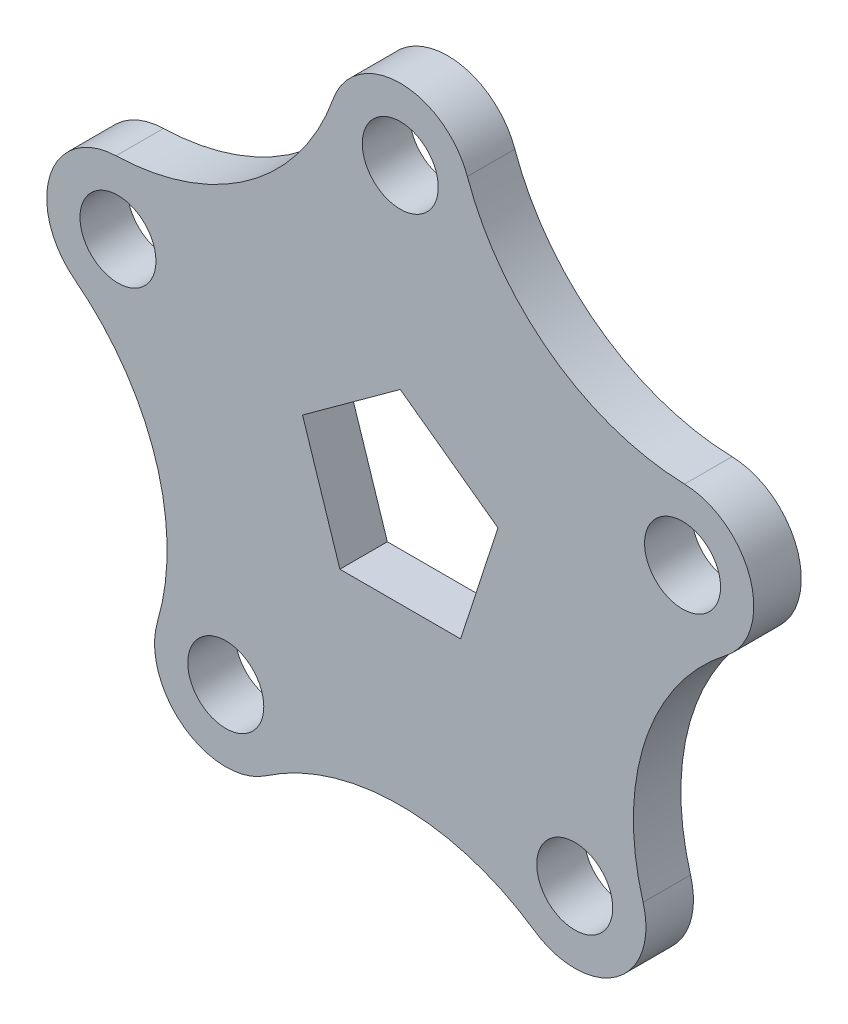
SolidWorks part; units mm, degrees
ref_plane "Front Plane" through (0, 0, 0) normal (0, 0, 1) x (1, 0, 0)
ref_plane "Top Plane" through (0, 0, 0) normal (0, 1, 0) x (1, 0, 0)
ref_plane "Right Plane" through (0, 0, 0) normal (1, 0, 0) x (0, 0, -1)
sketch "Sketch1" plane through (0, 0, 0) normal (0, 0, 1) x (1, 0, 0)
  line L0 (0, -55) -> (0, 55) construction
  line L1 (0, 21.6312) -> (-20.5725, 6.6844)
  line L2 (-20.5725, 6.6844) -> (-12.7145, -17.5)
  line L3 (-12.7145, -17.5) -> (12.7145, -17.5)
  line L4 (12.7145, -17.5) -> (20.5725, 6.6844)
  line L5 (20.5725, 6.6844) -> (0, 21.6312)
  circle A0 centre (0, 0) radius 17.5 construction
  circle A1 centre (0, 0) radius 62.5 construction
  circle A2 centre (0, 62.5) radius 8
  circle A3 centre (59.441, 19.3136) radius 8
  circle A4 centre (36.7366, -50.5636) radius 8
  circle A5 centre (-36.7366, -50.5636) radius 8
  circle A6 centre (-59.441, 19.3136) radius 8
  arc A7 (14.1321, 67.5282) -> (59.856, 34.3078) centre (61.2393, 84.2887) ccw
  arc A8 (14.1321, 67.5282) -> (-14.1321, 67.5282) centre (0, 62.5) ccw
  arc A9 (68.5902, 7.4269) -> (59.856, 34.3078) centre (59.441, 19.3136) ccw
  circle A10 centre (59.441, 19.3136) radius 15
  arc A11 (28.2589, -62.9381) -> (51.1252, -46.3248) centre (36.7366, -50.5636) ccw
  arc A12 (-51.1252, -46.3248) -> (-28.2589, -62.9381) centre (-36.7366, -50.5636) ccw
  arc A13 (-59.856, 34.3078) -> (-68.5902, 7.4269) centre (-59.441, 19.3136) ccw
  arc A14 (68.5902, 7.4269) -> (51.1252, -46.3248) centre (99.0873, -32.1954) ccw
  arc A15 (28.2589, -62.9381) -> (-28.2589, -62.9381) centre (0, -104.1865) ccw
  arc A16 (-51.1252, -46.3248) -> (-68.5902, 7.4269) centre (-99.0873, -32.1954) ccw
  arc A17 (-59.856, 34.3078) -> (-14.1321, 67.5282) centre (-61.2393, 84.2887) ccw
  point P24 (0, 0)
  point P37 (0, 0)
  point P44 (0, 0)
  dimension "D1" = 35
  dimension "D2" = 125
  dimension "D3" = 16
  dimension "D5" = 100
  dimension "D6" = 30
  dimension "D7" = 30
  dimension "D4" = 5
  dimension "D8" = 5
  dimension "D9" = 5
extrude "Boss-Extrude1" add sketch "Sketch1" along normal blind 10 contours A17 A13 A16 A12 A15 A11 A14 A10 A7 A8 A6 A5 A4 A2 L5 L4 L3 L2 L1 | A9 A10 A3
